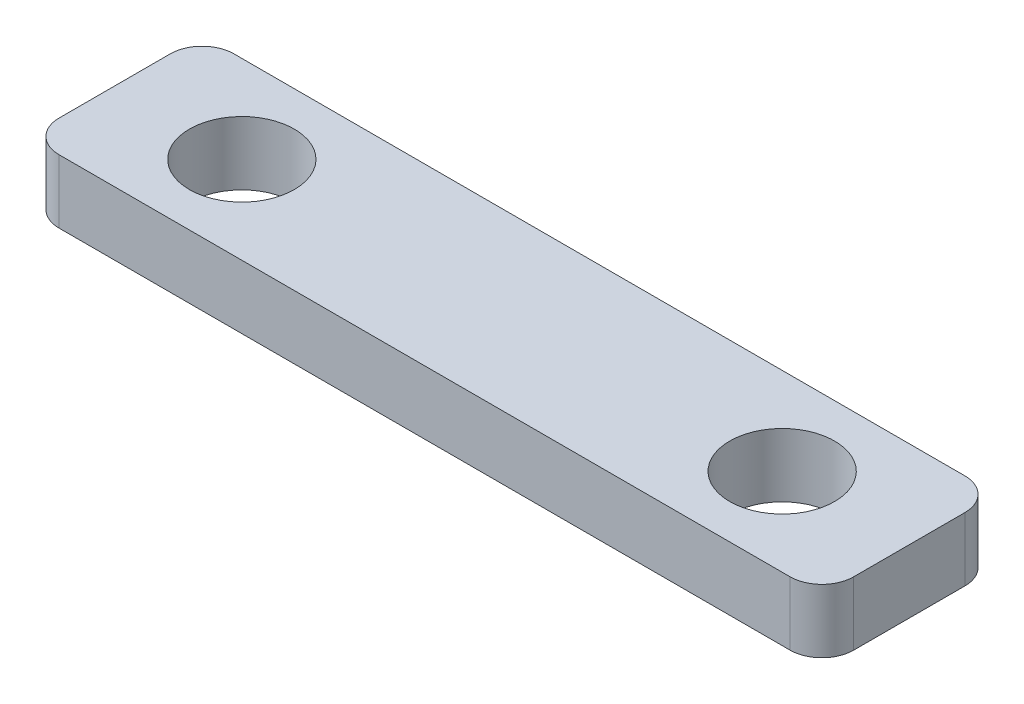
SolidWorks part; units mm, degrees
material "Beryllium Copper, UNS C17000"
ref_plane "Front Plane" through (0, 0, 0) normal (0, 0, 1) x (1, 0, 0)
ref_plane "Top Plane" through (0, 0, 0) normal (0, 1, 0) x (1, 0, 0)
ref_plane "Right Plane" through (0, 0, 0) normal (1, 0, 0) x (0, 0, -1)
sketch "Sketch1" plane through (0, 0, 0) normal (0, 1, 0) x (1, 0, 0)
  line L0 (4, 2.75) -> (21, 2.75) construction
  line L1 (0, 0) -> (25, 0)
  line L2 (0, 0) -> (0, 5.5)
  line L3 (0, 5.5) -> (25, 5.5)
  line L4 (25, 0) -> (25, 5.5)
  line L5 (21, 2.75) -> (25, 2.75) construction
  line L6 (4, 2.75) -> (0, 2.75) construction
  circle A0 centre (4, 2.75) radius 1.65
  circle A1 centre (21, 2.75) radius 1.65
  point P9 (2.4706, 2.4706)
  dimension "D1" = 3.3
  dimension "D2" = 4
  dimension "D3" = 5.5
  dimension "D4" = 25
extrude "Boss-Extrude1" add sketch "Sketch1" along normal blind 2
fillet "Fillet1" radius 1 4 edges at (0, 1, -5.5) (25, 1, -5.5) (25, 1, 0) (0, 1, 0)
